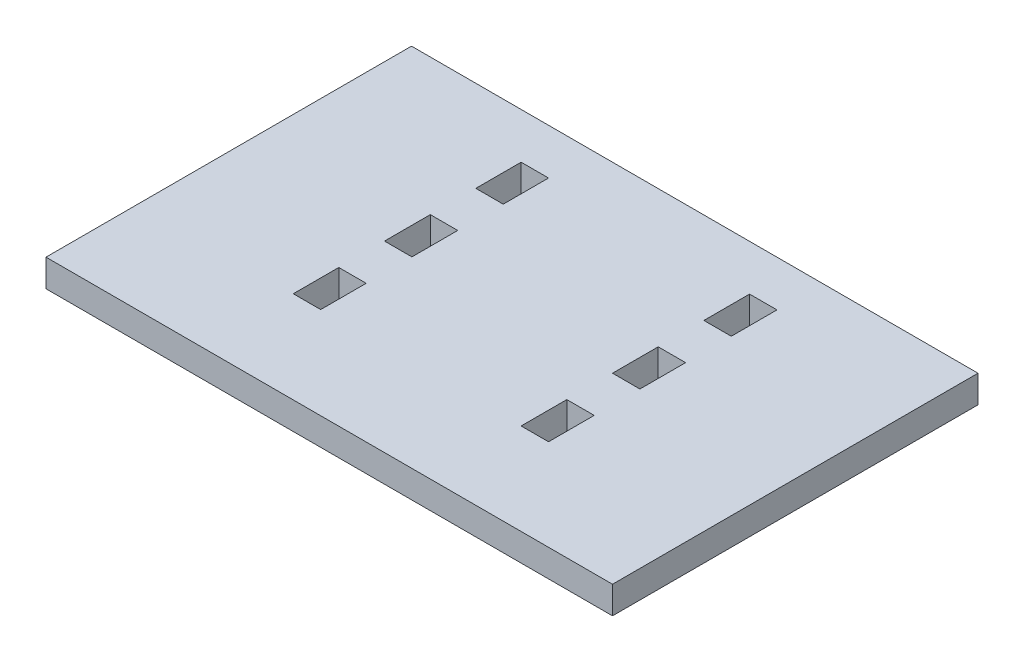
SolidWorks part; units mm, degrees
ref_plane "Front Plane" through (0, 0, 0) normal (0, 0, 1) x (1, 0, 0)
ref_plane "Top Plane" through (0, 0, 0) normal (0, 1, 0) x (1, 0, 0)
ref_plane "Right Plane" through (0, 0, 0) normal (1, 0, 0) x (0, 0, -1)
sketch "Sketch1" plane through (0, 0, 0) normal (0, 1, 0) x (1, 0, 0)
  line L1 (0, 0) -> (22, 0)
  line L2 (0, 0) -> (0, 40)
  line L3 (0, 40) -> (22, 40)
  line L4 (22, 0) -> (22, 40)
  line L5 (0, 40) -> (-20, 40)
  line L6 (0, 40) -> (0, 0)
  line L7 (0, 0) -> (-20, 0)
  line L8 (-20, 40) -> (-20, 0)
  line L9 (22, 40) -> (42, 40)
  line L10 (22, 40) -> (22, 0)
  line L11 (22, 0) -> (42, 0)
  line L12 (42, 40) -> (42, 0)
  line L20 (11, 40) -> (11, 0) construction
  line L21 (0, 35) -> (-3, 35)
  line L22 (0, 35) -> (0, 30.0397)
  line L23 (0, 30.0397) -> (-3, 30.0397)
  line L24 (-3, 35) -> (-3, 30.0397)
  line L29 (0, 25.0602) -> (-3, 25.0602)
  line L30 (0, 25.0602) -> (0, 20.0457)
  line L31 (0, 20.0457) -> (-3, 20.0457)
  line L32 (-3, 25.0602) -> (-3, 20.0457)
  line L37 (0, 15.0419) -> (-3, 15.0419)
  line L38 (0, 15.0419) -> (0, 10.0628)
  line L39 (0, 10.0628) -> (-3, 10.0628)
  line L40 (-3, 15.0419) -> (-3, 10.0628)
  line L54 (22, 35) -> (24.9981, 35)
  line L55 (22, 35) -> (22, 30)
  line L56 (22, 30) -> (24.9981, 30)
  line L57 (24.9981, 35) -> (24.9981, 30)
  line L62 (22, 25) -> (24.9981, 25)
  line L63 (22, 25) -> (22, 20)
  line L64 (22, 20) -> (24.9981, 20)
  line L65 (24.9981, 25) -> (24.9981, 20)
  line L70 (22, 15) -> (24.9981, 15)
  line L71 (22, 15) -> (22, 10)
  line L72 (22, 10) -> (24.9981, 10)
  line L73 (24.9981, 15) -> (24.9981, 10)
  dimension "D1" = 22
  dimension "D2" = 40
  dimension "D3" = 20
  dimension "D4" = 20
  dimension "D5" = 3
  dimension "D6" = 27.9981
  dimension "D7" = 29.9372
  dimension "D9" = 5
  dimension "D11" = 5
  dimension "D12" = 5
  dimension "D13" = 5
extrude "Boss-Extrude1" add sketch "Sketch1" along normal blind 3 contours L20 L3 L6 L2 L1 | L40 L37 L6 L31 L32 L29 L23 L24 L21 L5 L8 L7 L2 L39 | L3 L20 L1 L4 L10 | L70 L73 L72 L4 L11 L12 L9 L10 L54 L57 L56 L62 L65 L64
